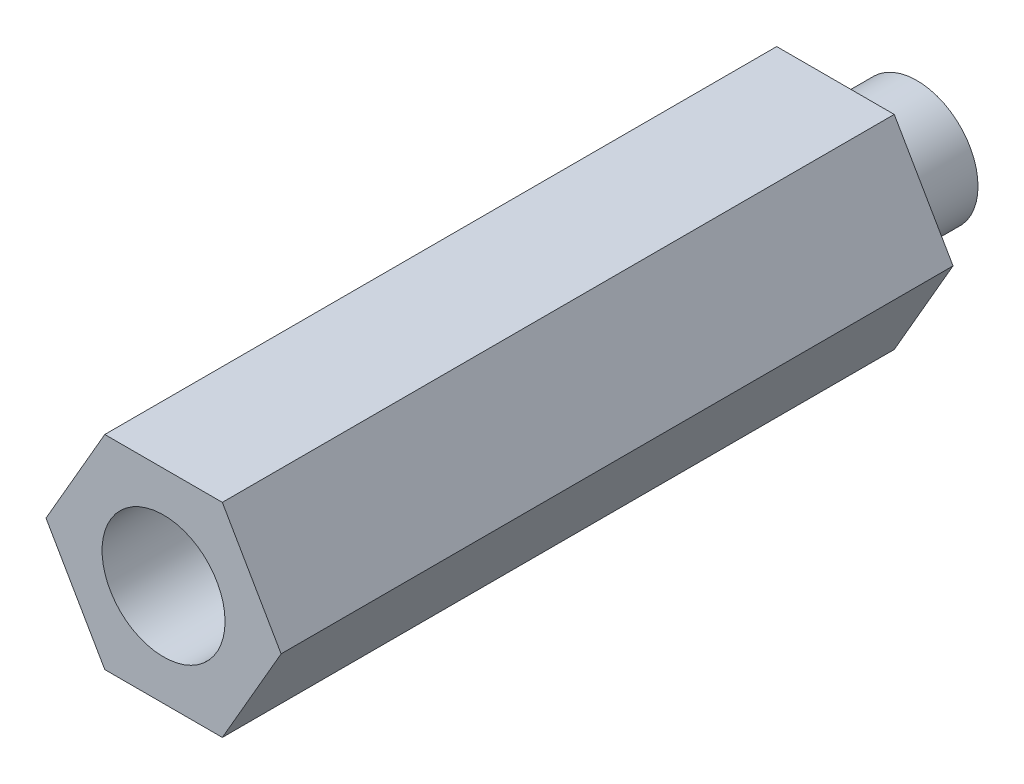
SolidWorks part; units mm, degrees
ref_plane "前视基准面" through (0, 0, 0) normal (0, 0, 1) x (1, 0, 0)
ref_plane "上视基准面" through (0, 0, 0) normal (0, 1, 0) x (1, 0, 0)
ref_plane "右视基准面" through (0, 0, 0) normal (1, 0, 0) x (0, 0, -1)
other "Configuration Table"
sketch "Female_M3_hex_standoff_AF5_Sketch" plane through (0, 0, 0) normal (0, 0, 1) x (1, 0, 0)
  line L0 (2.8868, 0) -> (1.4434, 2.5)
  line L1 (1.4434, 2.5) -> (-1.4434, 2.5)
  line L2 (-1.4434, 2.5) -> (-2.8868, 0)
  line L3 (-2.8868, 0) -> (-1.4434, -2.5)
  line L4 (-1.4434, -2.5) -> (1.4434, -2.5)
  line L5 (1.4434, -2.5) -> (2.8868, 0)
  circle A0 centre (0, 0) radius 1.51
extrude "Female_M3_hex_standoff_AF5" add sketch "Female_M3_hex_standoff_AF5_Sketch" along normal blind 16.5 separate body
sketch "Stud_root_Sketch" plane through (0, 0, 0) normal (0, 0, 1) x (1, 0, 0)
  circle A0 centre (0, 0) radius 1.85
extrude "Stud_root" add sketch "Stud_root_Sketch" along normal blind 0.45
sketch "Male_M3_stud_envelope_Sketch" plane through (0, 0, 0) normal (0, 0, 1) x (1, 0, 0)
  circle A0 centre (0, 0) radius 1.5
extrude "Male_M3_stud_envelope" add sketch "Male_M3_stud_envelope_Sketch" along normal blind 2 from offset 2
